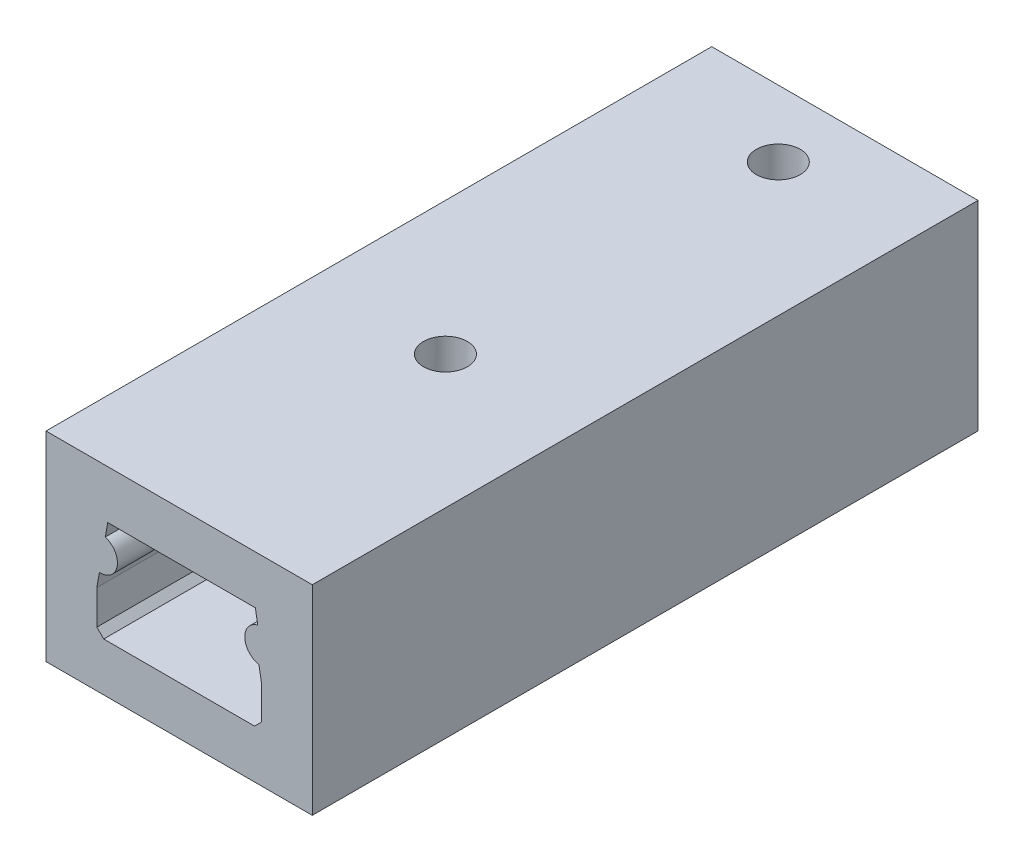
SolidWorks part; units mm, degrees
ref_plane "Front Plane" through (0, 0, 0) normal (0, 0, 1) x (1, 0, 0)
ref_plane "Top Plane" through (0, 0, 0) normal (0, 1, 0) x (1, 0, 0)
ref_plane "Right Plane" through (0, 0, 0) normal (1, 0, 0) x (0, 0, -1)
sketch "Sketch2" plane through (0, 0, 0) normal (0, 0, 1) x (1, 0, 0)
  line L0 (0.18, -0.3375) -> (0.18, 7.6125) construction
  line L2 (-10, -3.75) -> (10, -3.75)
  line L3 (-10, -3.75) -> (-10, 11.25)
  line L4 (-10, 11.25) -> (10, 11.25)
  line L5 (10, -3.75) -> (10, 11.25)
  line L6 (-10, -3.75) -> (10, 11.25) construction
  line L7 (-10, 11.25) -> (10, -3.75) construction
  line L20 (6.18, 0.4025) -> (6.18, 2.9775)
  line L21 (6.18, 2.9775) -> (5.989, 4.0607)
  line L22 (5.9052, 6.5775) -> (5.7227, 7.6125)
  line L23 (5.7227, 7.6125) -> (-5.3627, 7.6125)
  line L24 (-5.3627, 7.6125) -> (-5.5452, 6.5775)
  line L25 (-5.989, 4.0607) -> (-6.18, 2.9775)
  line L26 (-6.18, 2.9775) -> (-6.18, 0.4025)
  line L27 (-6.18, 0.4025) -> (-5.665, -0.1125)
  line L28 (-5.665, -0.1125) -> (5.665, -0.1125)
  line L29 (5.665, -0.1125) -> (6.18, 0.4025)
  arc A4 (5.9052, 6.5775) -> (5.989, 4.0607) centre (6.216, 5.3281) ccw
  arc A5 (-5.989, 4.0607) -> (-5.5452, 6.5775) centre (-5.9225, 5.3465) ccw
  point P9 (0.18, 3.6375)
  dimension "D1" = 15
  dimension "D2" = 20
  dimension "D3" = 3.75
  dimension "D4" = 6
extrude "Boss-Extrude1" add sketch "Sketch2" along normal blind 50
sketch "Sketch3" plane through (0, 11.25, 0) normal (0, 1, 0) x (1, 0, 0)
  line L0 (0, 0) -> (0, -51.3909) construction
  line L1 (10, 0) -> (-10, 0) construction
  circle A0 centre (0, -5) radius 1.65
  circle A1 centre (0, -30) radius 1.65
  dimension "D1" = 5
  dimension "D2" = 3.3
  dimension "D3" = 25
extrude "Cut-Extrude1" cut sketch "Sketch3" against normal through all
